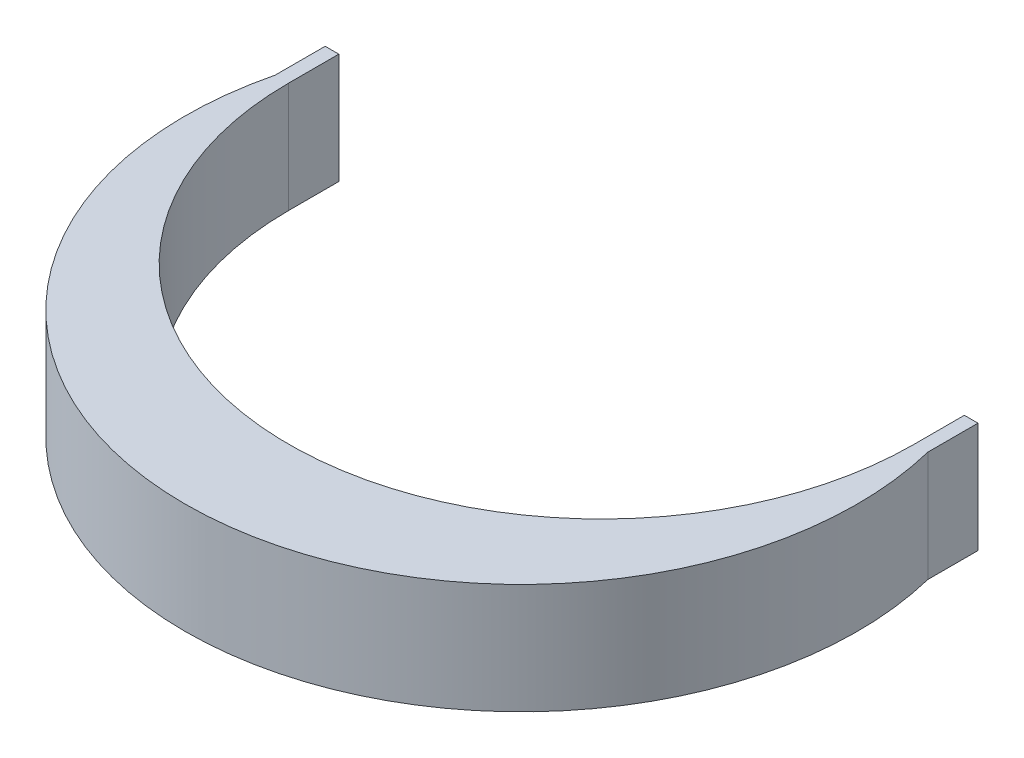
SolidWorks part; units mm, degrees
ref_plane "Front Plane" through (0, 0, 0) normal (0, 0, 1) x (1, 0, 0)
ref_plane "Top Plane" through (0, 0, 0) normal (0, 1, 0) x (1, 0, 0)
ref_plane "Right Plane" through (0, 0, 0) normal (1, 0, 0) x (0, 0, -1)
sketch "Sketch1" plane through (0, 0, 0) normal (0, 0, 1) x (1, 0, 0)
  line L1 (0, 0) -> (-0.34, 0)
  line L2 (0, 0) -> (0, 2.75)
  line L3 (0, 2.75) -> (-0.34, 2.75)
  line L4 (-0.34, 0) -> (-0.34, 2.75)
  line L5 (15.59, 2.75) -> (15.93, 2.75)
  line L6 (15.59, 2.75) -> (15.59, 0)
  line L7 (15.59, 0) -> (15.93, 0)
  line L8 (15.93, 2.75) -> (15.93, 0)
  dimension "D1" = 0.34
  dimension "D2" = 2.75
  dimension "D3" = 15.59
  dimension "D4" = 0.34
  dimension "D5" = 2.75
extrude "Boss-Extrude1" add sketch "Sketch1" along normal blind 1.25
sketch "Sketch2" plane through (0, 2.75, 0) normal (0, 1, 0) x (1, 0, 0)
  line L1 (15.59, -1.25) -> (15.59, 0) construction
  line L2 (-0.34, -1.25) -> (0, -1.25)
  line L3 (15.59, -1.25) -> (15.93, -1.25)
  arc A1 (0, -1.25) -> (15.59, -1.25) centre (7.795, -1.25) ccw
  arc A2 (-0.34, -1.25) -> (15.93, -1.25) centre (7.795, -3.25) ccw
  dimension "D1" = 2
extrude "Boss-Extrude2" add sketch "Sketch2" against normal up to surface (2.75 mm away) up to face at (-0.17, 0, 0.625)
